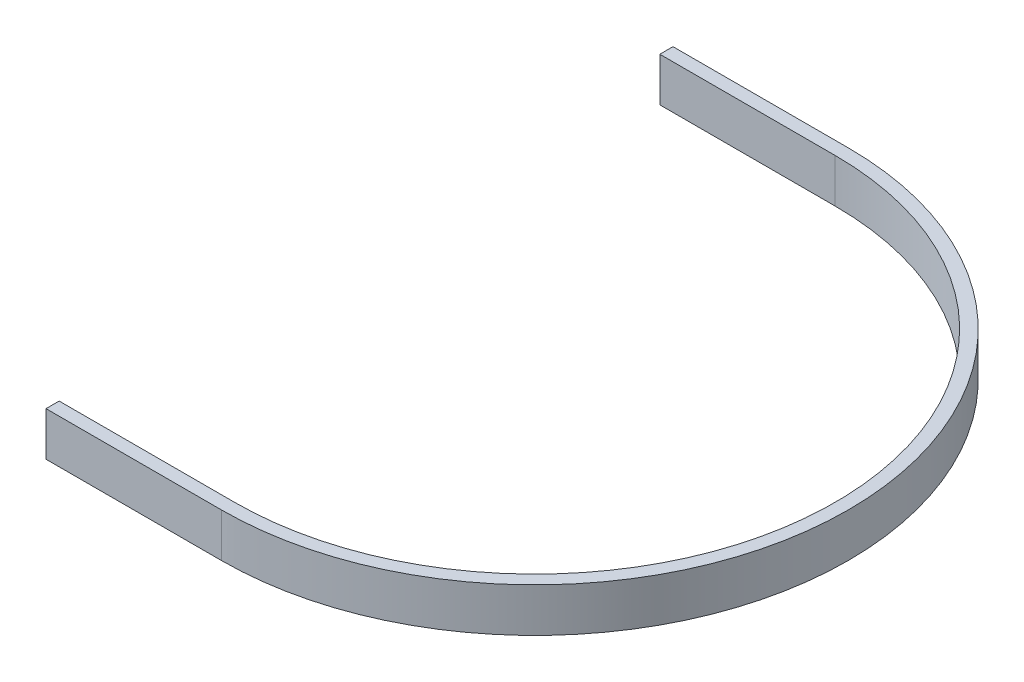
SolidWorks part; units mm, degrees
ref_plane "Plan de face" through (0, 0, 0) normal (0, 0, 1) x (1, 0, 0)
ref_plane "Plan de dessus" through (0, 0, 0) normal (0, 1, 0) x (1, 0, 0)
ref_plane "Plan de droite" through (0, 0, 0) normal (1, 0, 0) x (0, 0, -1)
sketch "Esquisse2" plane through (0, 0, 0) normal (0, 1, 0) x (1, 0, 0)
  line L0 (0, 68.5) -> (0, -68.5)
  line L1 (0, 68.5) -> (0, 71.5)
  line L2 (0, -68.5) -> (0, -71.5)
  circle A0 centre (0, 0) radius 68.5
  circle A1 centre (0, 0) radius 71.5
  dimension "D1" = 137
  dimension "D2" = 3
  dimension "D3" = 137
extrude "Boss.-Extru.1" add sketch "Esquisse2" along normal blind 10 contours L2 A1 L1 A0
sketch "Esquisse3" plane through (0, 0, 0) normal (-1, 0, 0) x (0, 0, 1)
  line L1 (-68.5, 10) -> (-71.5, 10)
  line L2 (-68.5, 10) -> (-68.5, 0)
  line L3 (-68.5, 0) -> (-71.5, 0)
  line L4 (-71.5, 10) -> (-71.5, 0)
  line L5 (71.5, 10) -> (68.5, 10)
  line L6 (71.5, 10) -> (71.5, 0)
  line L7 (71.5, 0) -> (68.5, 0)
  line L8 (68.5, 10) -> (68.5, 0)
extrude "Boss.-Extru.2" add sketch "Esquisse3" along normal blind 40
